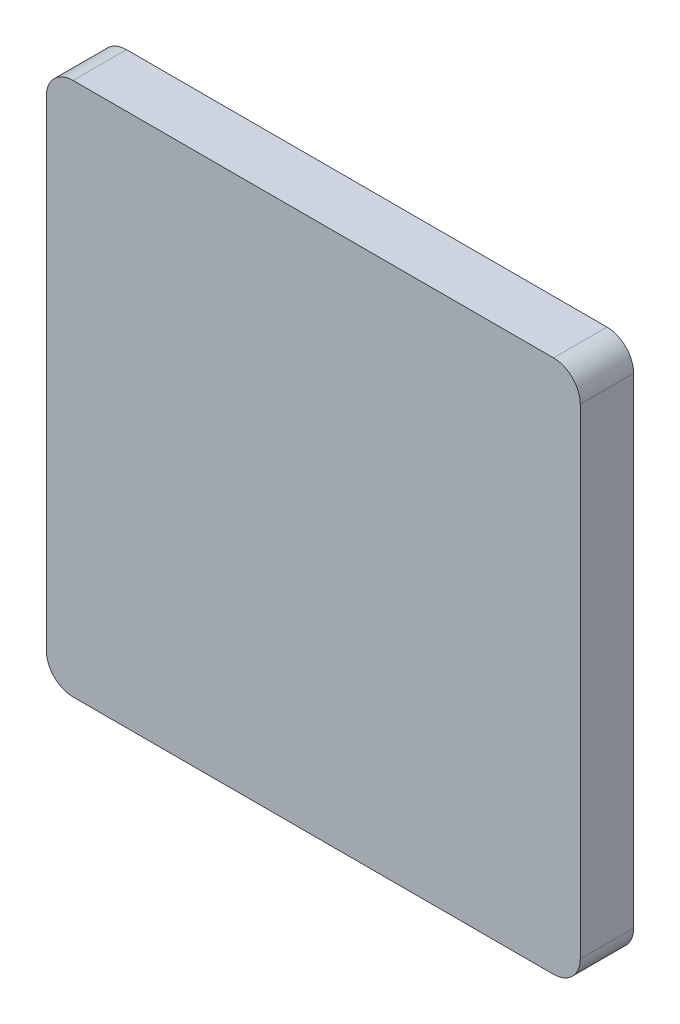
SolidWorks part; units mm, degrees
material "Rubber"
ref_plane "Front Plane" through (0, 0, 0) normal (0, 0, 1) x (1, 0, 0)
ref_plane "Top Plane" through (0, 0, 0) normal (0, 1, 0) x (1, 0, 0)
ref_plane "Right Plane" through (0, 0, 0) normal (1, 0, 0) x (0, 0, -1)
sketch "Sketch1" plane through (0, 0, 0) normal (0, 0, 1) x (1, 0, 0)
  line L1 (-10, 10) -> (10, 10)
  line L2 (-10, 10) -> (-10, -10)
  line L3 (-10, -10) -> (10, -10)
  line L4 (10, 10) -> (10, -10)
  line L5 (-10, 10) -> (10, -10) construction
  line L6 (-10, -10) -> (10, 10) construction
  point P0 (0, 0)
  dimension "D1" = 20
  dimension "D2" = 20
extrude "Boss-Extrude1" add sketch "Sketch1" along normal blind 2
fillet "Fillet1" radius 1 4 edges at (10, -10, 1) (-10, -10, 1) (-10, 10, 1) (10, 10, 1)
